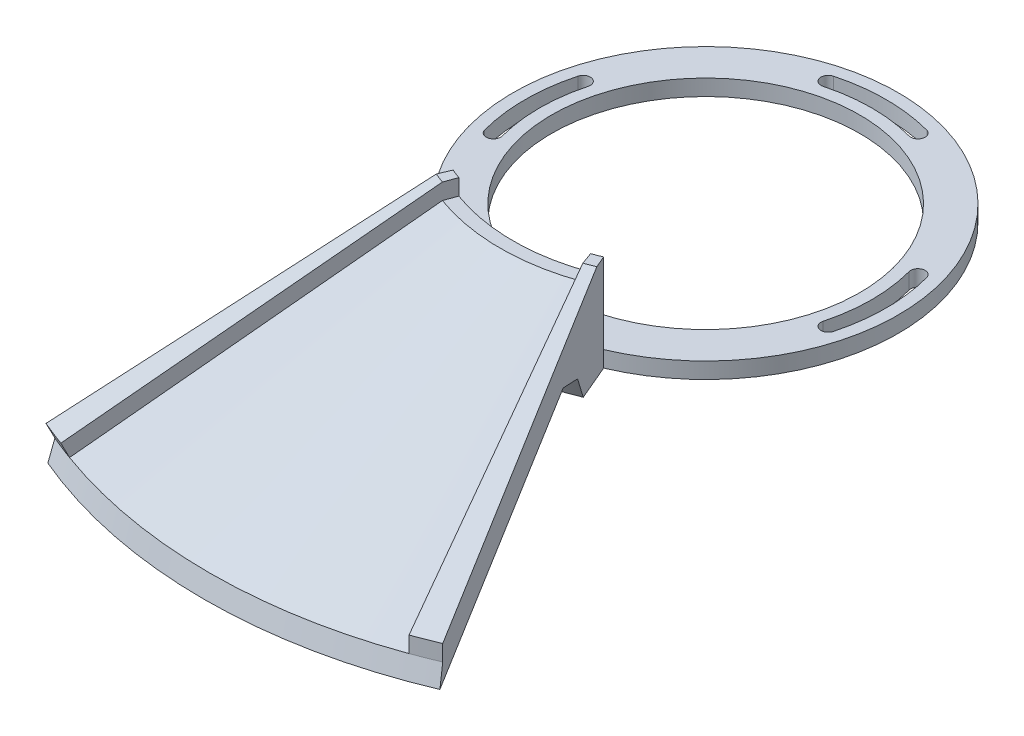
SolidWorks part; units mm, degrees
ref_plane "Piano frontale" through (0, 0, 0) normal (0, 0, 1) x (1, 0, 0)
ref_plane "Piano superiore" through (0, 0, 0) normal (0, 1, 0) x (1, 0, 0)
ref_plane "Piano destro" through (0, 0, 0) normal (1, 0, 0) x (0, 0, -1)
sketch "Schizzo1" plane through (0, 0, 0) normal (0, 1, 0) x (1, 0, 0)
  line L0 (0, -60) -> (0, 60) construction
  line L1 (-60, 0) -> (60, 0) construction
  line L2 (-13.9762, 52.16) -> (0, 0) construction
  line L3 (0, 0) -> (13.9762, 52.16) construction
  line L4 (-52.16, 13.9762) -> (0, 0) construction
  line L5 (0, 0) -> (-52.16, -13.9762) construction
  line L6 (-13.9762, -52.16) -> (0, 0) construction
  line L7 (0, 0) -> (13.9762, -52.16) construction
  line L8 (52.16, -13.9762) -> (0, 0) construction
  line L9 (0, 0) -> (52.16, 13.9762) construction
  line L10 (-40, -160) -> (-40, -44.7214)
  line L11 (20, -160) -> (20, -56.5685)
  line L12 (-40, -160) -> (20, -160)
  circle A0 centre (0, 0) radius 60
  circle A1 centre (0, 0) radius 48
  arc A2 (14.5586, 54.3333) -> (-14.5586, 54.3333) centre (0, 0) ccw
  arc A3 (13.3939, 49.9867) -> (-13.3939, 49.9867) centre (0, 0) ccw
  arc A4 (16.137, 51.5325) -> (-16.137, 51.5325) centre (0, 0) ccw construction
  arc A5 (-14.5586, 54.3333) -> (-13.3939, 49.9867) centre (-13.9762, 52.16) ccw
  arc A6 (13.3939, 49.9867) -> (14.5586, 54.3333) centre (13.9762, 52.16) ccw
  arc A7 (-54.3333, -14.5586) -> (-49.9867, -13.3939) centre (-52.16, -13.9762) ccw
  arc A8 (-49.9867, 13.3939) -> (-54.3333, 14.5586) centre (-52.16, 13.9762) ccw
  arc A9 (-13.3939, -49.9867) -> (-14.5586, -54.3333) centre (-13.9762, -52.16) ccw
  arc A10 (14.5586, -54.3333) -> (13.3939, -49.9867) centre (13.9762, -52.16) ccw
  arc A11 (49.9867, -13.3939) -> (54.3333, -14.5586) centre (52.16, -13.9762) ccw
  arc A12 (54.3333, 14.5586) -> (49.9867, 13.3939) centre (52.16, 13.9762) ccw
  arc A13 (54.3333, -14.5586) -> (54.3333, 14.5586) centre (0, 0) ccw
  arc A14 (51.5325, -16.137) -> (51.5325, 16.137) centre (0, 0) ccw construction
  arc A15 (49.9867, -13.3939) -> (49.9867, 13.3939) centre (0, 0) ccw
  arc A16 (-13.3939, -49.9867) -> (13.3939, -49.9867) centre (0, 0) ccw
  arc A17 (-16.137, -51.5325) -> (16.137, -51.5325) centre (0, 0) ccw construction
  arc A18 (-14.5586, -54.3333) -> (14.5586, -54.3333) centre (0, 0) ccw
  arc A19 (-54.3333, 14.5586) -> (-54.3333, -14.5586) centre (0, 0) ccw
  arc A20 (-51.5325, 16.137) -> (-51.5325, -16.137) centre (0, 0) ccw construction
  arc A21 (-49.9867, 13.3939) -> (-49.9867, -13.3939) centre (0, 0) ccw
  dimension "D1" = 120
  dimension "D2" = 12
  dimension "D3" = 60
  dimension "D4" = 6
  dimension "D5" = 15
  dimension "D6" = 15
  dimension "D7" = 15
  dimension "D8" = 15
  dimension "D9" = 15
  dimension "D10" = 15
  dimension "D11" = 15
  dimension "D12" = 15
  dimension "D13" = 20
  dimension "D14" = 160
extrude "Estrusione-Estrusione1" add sketch "Schizzo1" along normal blind 5 contours A0 A18 A9 A16 A10 A6 A3 A5 A2 A1 A11 A15 A12 A13 A8 A21 A7 A19
ref_axis "Assi1" through (0, 115.2992, 0) along (0, -1, 0)
sketch "Schizzo2" plane through (0, 0, 0) normal (-1, 0, 0) x (0, 0, 1)
  line L0 (83.8013, 10.2496) -> (156.3059, -23.5599)
  line L2 (156.3059, -23.5599) -> (154.6308, -17.2618)
  line L3 (154.6308, -17.2618) -> (64, 25)
  line L5 (0, 115.2992) -> (0, -234.67) construction
  line L8 (60, 25) -> (64, 25)
  line L9 (60, 25) -> (60, 0)
  line L16 (60, 0) -> (72, 0)
  line L17 (72, 0) -> (75.3441, 7.1714)
  line L18 (75.3441, 7.1714) -> (83.8013, 10.2496)
  dimension "D1" = 25
  dimension "D2" = 4
  dimension "D3" = 5
  dimension "D4" = 25
  dimension "D5" = 12
  dimension "D6" = 45
  dimension "D7" = 9
  dimension "D8" = 60
  dimension "D9" = 80
  dimension "D10" = 100
revolve "Rivoluzione1" add sketch "Schizzo2" angle 23 about axis through (0, 115.2992, 0) along (0, -1, 0) other way angle 23
sketch "Schizzo3" plane through (0, 0, 0) normal (-0.9205, 0, -0.3907) x (-0.3907, 0, 0.9205)
  line L0 (60, 25) -> (60, 30)
  line L1 (60, 25) -> (64, 25)
  line L2 (64, 25) -> (154.6308, -17.2618)
  line L3 (154.6308, -17.2618) -> (156.7439, -12.7303)
  line L4 (156.7439, -12.7303) -> (64, 30)
  line L5 (64, 30) -> (60, 30)
  dimension "D1" = 5
  dimension "D2" = 4
  dimension "D3" = 5
revolve "Rivoluzione2" add sketch "Schizzo3" angle 3 about axis through (0, 115.2992, 0) along (0, -1, 0)
sketch "Schizzo4" plane through (0, 0, 0) normal (0.9205, 0, -0.3907) x (-0.3907, 0, -0.9205)
  line L6 (-60, 25) -> (-64, 25)
  line L7 (-64, 25) -> (-154.6308, -17.2618)
  line L8 (-154.6308, -17.2618) -> (-154.6308, -12.2618)
  line L9 (-154.6308, -12.2618) -> (-64, 30)
  line L10 (-64, 30) -> (-60, 30)
  line L11 (-60, 30) -> (-60, 25)
  dimension "D1" = 5
  dimension "D2" = 5
  dimension "D3" = 4
revolve "Rivoluzione3" add sketch "Schizzo4" angle 3 about axis through (0, 115.2992, 0) along (0, -1, 0)
